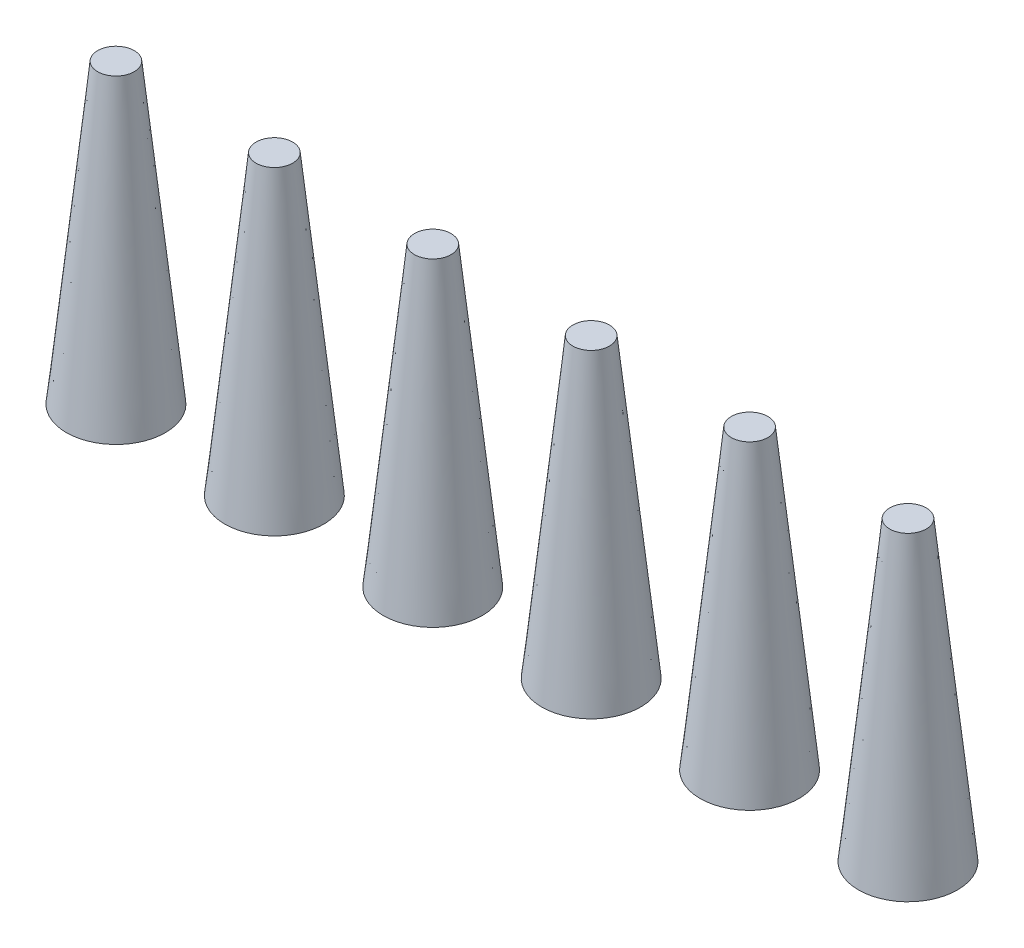
SolidWorks part; units mm, degrees
ref_plane "Front Plane" through (0, 0, 0) normal (0, 0, 1) x (1, 0, 0)
ref_plane "Top Plane" through (0, 0, 0) normal (0, 1, 0) x (1, 0, 0)
ref_plane "Right Plane" through (0, 0, 0) normal (1, 0, 0) x (0, 0, -1)
sketch "Sketch1" plane through (0, 0, 0) normal (0, 1, 0) x (1, 0, 0)
  circle A0 centre (0, 0) radius 2.5
  circle A1 centre (8, 0) radius 2.5
  circle A2 centre (16, 0) radius 2.5
  circle A3 centre (24, 0) radius 2.5
  circle A4 centre (32, 0) radius 2.5
  circle A5 centre (40, 0) radius 2.5
  dimension "D1" = 5
  dimension "D2" = 6
extrude "Boss-Extrude1" add sketch "Sketch1" along normal blind 15 draft 6
